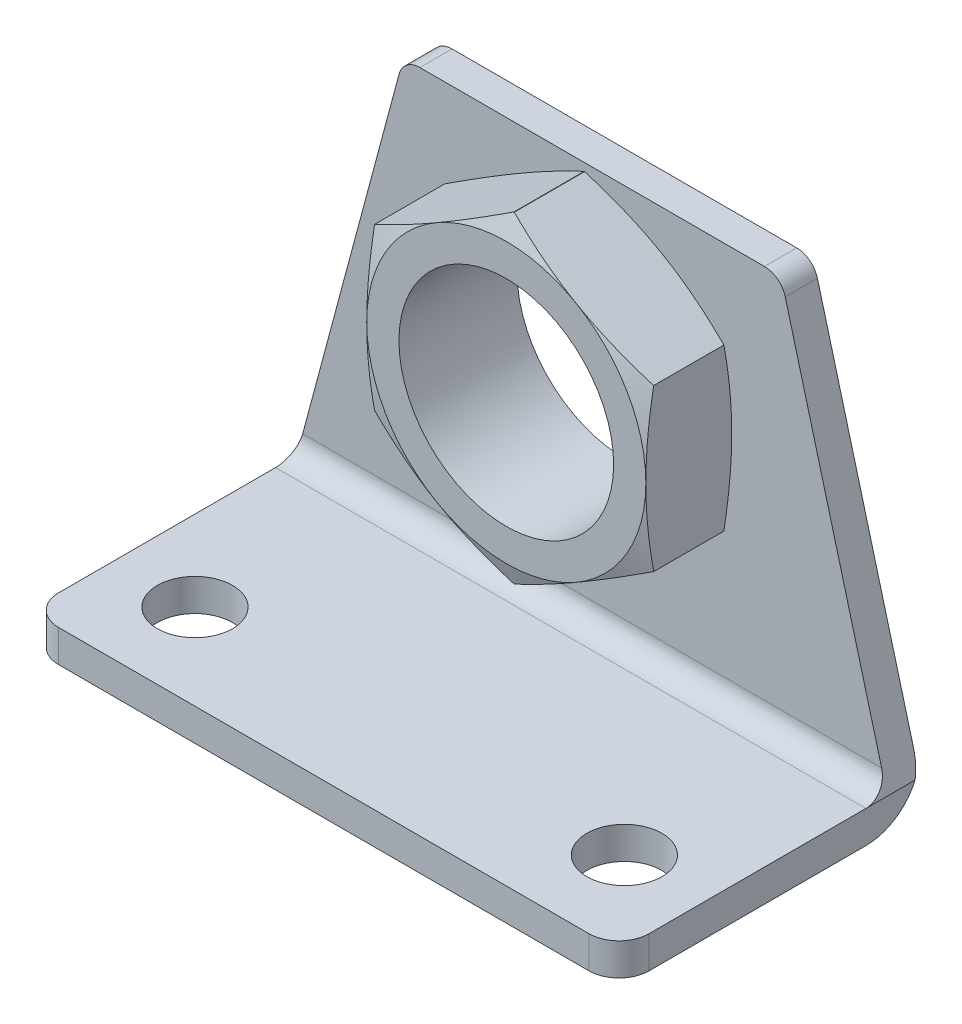
SolidWorks part; units mm, degrees
ref_plane "前视基准面" through (0, 0, 0) normal (0, 0, 1) x (1, 0, 0)
ref_plane "上视基准面" through (0, 0, 0) normal (0, 1, 0) x (1, 0, 0)
ref_plane "右视基准面" through (0, 0, 0) normal (1, 0, 0) x (0, 0, -1)
sketch "草图1" plane through (0, 0, 0) normal (0, 0, 1) x (1, 0, 0)
  line L0 (0, 0) -> (0, 40) construction
  line L1 (-27.5, 0) -> (27.5, 0) construction
  line L2 (0, 25) -> (8, 25) construction
  line L3 (0, 40.0111) -> (-13, 32.5056)
  line L4 (-13, 32.5056) -> (-13, 17.4944)
  line L5 (-13, 17.4944) -> (0, 9.9889)
  line L6 (0, 9.9889) -> (13, 17.4944)
  line L7 (13, 17.4944) -> (13, 32.5056)
  line L8 (13, 32.5056) -> (0, 40.0111)
  circle A0 centre (0, 25) radius 10
  circle A1 centre (0, 25) radius 13 construction
  point P5 (-20, 0)
  dimension "L" = 20
  dimension "缸体T1" = 26
  dimension "BE" = 55
  dimension "BF" = 40
  dimension "BH" = 40
  dimension "BG" = 25
  dimension "缸体M" = 8
sketch "草图2" plane through (0, 0, 0) normal (1, 0, 0) x (0, 0, -1)
  line L0 (0, 0) -> (-28, 0) construction
  line L1 (-20, 0) -> (-20, 3) construction
  point P5 (-16.5, 0)
  dimension "BB" = 3
  dimension "BD" = 8
  dimension "BC" = 20
  dimension "AA" = 7
sketch "草图3" plane through (0, 0, 0) normal (1, 0, 0) x (0, 0, -1)
  line L0 (-28, 0) -> (-5, 0)
  line L1 (0, 5) -> (0, 40)
  line L2 (0, 0) -> (0, 40) construction
  line L3 (-28, 0) -> (-28, 3)
  line L4 (-28, 3) -> (-5, 3)
  line L5 (-3, 5) -> (-3, 40)
  line L6 (-3, 40) -> (0, 40)
  arc A0 (-5, 3) -> (-3, 5) centre (-5, 5) ccw
  arc A1 (-5, 0) -> (0, 5) centre (-5, 5) ccw
  dimension "D1" = 4
extrude "凸台-拉伸1" add sketch "草图3" against normal up to vertex (27.5 mm away) from vertex at 27.5 starting at point (27.5, 0, 0)
sketch "草图7" plane through (0, 0, 3) normal (0, 0, 1) x (1, 0, 0)
  line L0 (0, 40.0111) -> (-13, 32.5056) construction
  line L1 (-13, 32.5056) -> (-13, 17.4944) construction
  line L2 (-13, 17.4944) -> (0, 9.9889) construction
  line L3 (0, 9.9889) -> (13, 17.4944) construction
  line L4 (13, 17.4944) -> (13, 32.5056) construction
  line L5 (13, 32.5056) -> (0, 40.0111) construction
  line L6 (0, 40.0111) -> (-13, 32.5056)
  line L7 (-13, 32.5056) -> (-13, 17.4944)
  line L8 (-13, 17.4944) -> (0, 9.9889)
  line L9 (0, 9.9889) -> (13, 17.4944)
  line L10 (13, 17.4944) -> (13, 32.5056)
  line L11 (13, 32.5056) -> (0, 40.0111)
extrude "凸台-拉伸2" add sketch "草图7" along normal blind 8
ref_plane "基准面1" through (0, 25, 0) normal (0, 1, 0) x (-1, 0, 0)
sketch "草图4" plane through (0, 0, 3) normal (0, 0, 1) x (1, 0, 0)
  circle A0 centre (0, 25) radius 10 construction
  circle A1 centre (0, 25) radius 10
extrude "切除-拉伸1" cut sketch "草图4" against normal through all and the other way through all
sketch "草图8" plane through (0, 25, 0) normal (0, 1, 0) x (-1, 0, 0)
  line L0 (-13, 7) -> (0, 7) construction
  line L1 (-13, 11) -> (-13, 3) construction
  line L2 (0, 11) -> (0, 3) construction
  line L3 (-13, 11) -> (-18, 11)
  line L4 (-13, 11) -> (-18, 9.1801)
  line L5 (-18, 11) -> (-18, 9.1801)
  line L6 (-18, 3) -> (-18, 4.8199)
  line L7 (-13, 3) -> (-18, 4.8199)
  line L8 (-13, 3) -> (-18, 3)
  dimension "D1" = 20
  dimension "D2" = 5
revolve "切除-旋转1" cut sketch "草图8" angle 360 mid plane about axis through (0, 25, 0) along (0, 0, 1)
sketch "草图5" plane through (0, 0, 3) normal (0, 0, 1) x (1, 0, 0)
  line L0 (-17.5859, 40) -> (-27.5, 3)
  line L1 (-27.5, 40) -> (27.5, 40) construction
  line L2 (0, 0) -> (0, 25) construction
  line L3 (17.5859, 40) -> (27.5, 3)
  line L4 (-27.5, 3) -> (-27.5, 50)
  line L5 (-27.5, 50) -> (27.5, 50)
  line L6 (27.5, 50) -> (27.5, 3)
  line L7 (-17.5859, 40) -> (17.5859, 40)
  dimension "D1" = 30
  dimension "D2" = 10
extrude "切除-拉伸2" cut sketch "草图5" against normal through all and the other way through all
sketch "草图6" plane through (0, 3, 0) normal (0, 1, 0) x (1, 0, 0)
  line L0 (0, 0) -> (0, -16.5) construction
  circle A0 centre (-20, -20) radius 3.5
  circle A1 centre (20, -20) radius 3.5
  point P2 (-20, -16.5)
  point P11 (20, -16.5)
extrude "切除-拉伸3" cut sketch "草图6" against normal through all
fillet "圆角1" radius 2 2 edges at (17.5859, 40, 1.5) (-17.5859, 40, 1.5)
fillet "圆角2" radius 2.8 2 edges at (27.5, 1.5, 28) (-27.5, 1.5, 28)
